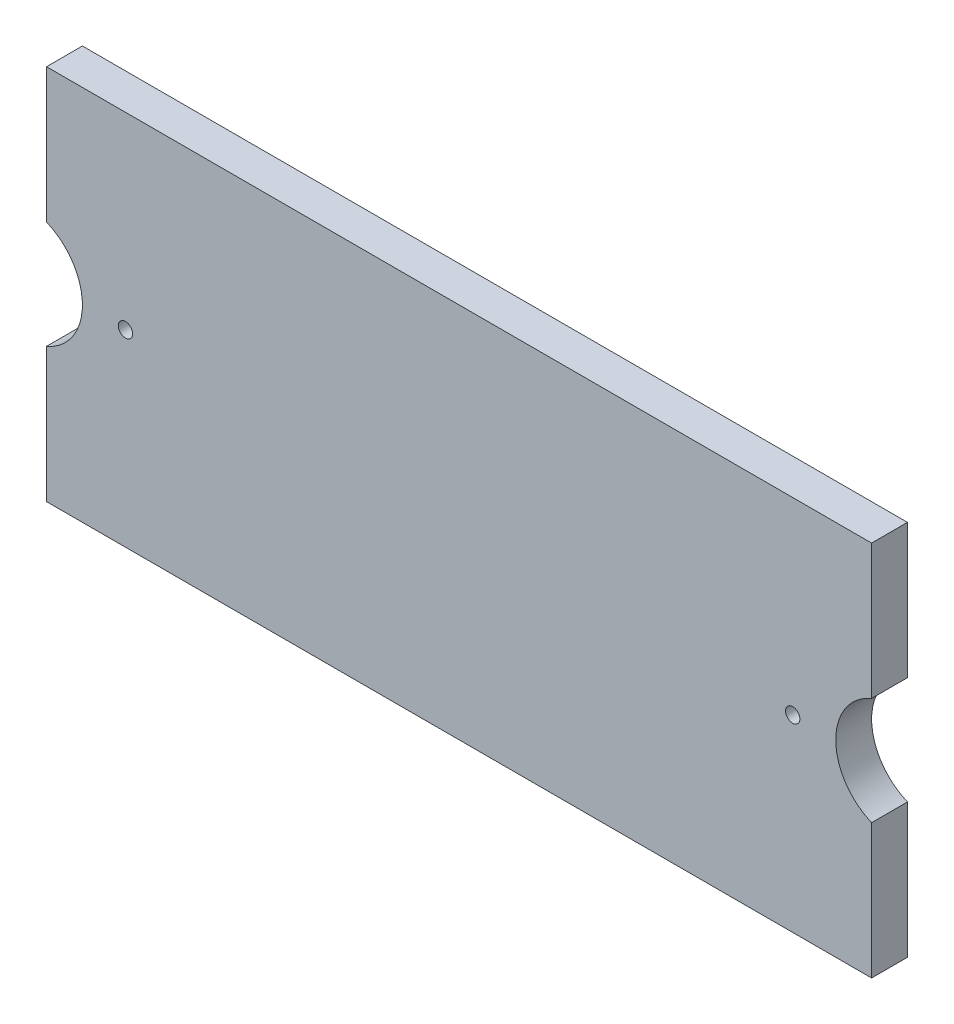
SolidWorks part; units mm, degrees
ref_plane "Front Plane" through (0, 0, 0) normal (0, 0, 1) x (1, 0, 0)
ref_plane "Top Plane" through (0, 0, 0) normal (0, 1, 0) x (1, 0, 0)
ref_plane "Right Plane" through (0, 0, 0) normal (1, 0, 0) x (0, 0, -1)
sketch "Sketch1" plane through (0, 0, 0) normal (0, 0, 1) x (1, 0, 0)
  line L0 (115, 105) -> (115, -12.2356) construction
  line L1 (0, 0) -> (230, 0)
  line L2 (0, 0) -> (0, 37.5)
  line L3 (0, 105) -> (230, 105)
  line L4 (230, 0) -> (230, 37.5)
  line L5 (0, 52.5) -> (283.1054, 52.5) construction
  line L6 (220, 69.6094) -> (220, 35.6718) construction
  line L7 (230, 67.5) -> (230, 105)
  line L8 (0, 67.5) -> (0, 105)
  arc A0 (230, 67.5) -> (230, 37.5) centre (236.25, 52.5) ccw
  circle A1 centre (208, 52.5) radius 2
  circle A2 centre (22, 52.5) radius 2
  arc A3 (0, 67.5) -> (0, 37.5) centre (-6.25, 52.5) cw
  point P21 (0, 67.5029)
  dimension "D3" = 10
  dimension "D5" = 4
  dimension "D6" = 22
  dimension "D1" = 230
  dimension "D2" = 105
  dimension "D4" = 30
  dimension "D7" = 52.5
extrude "Boss-Extrude1" add sketch "Sketch1" along normal blind 10
